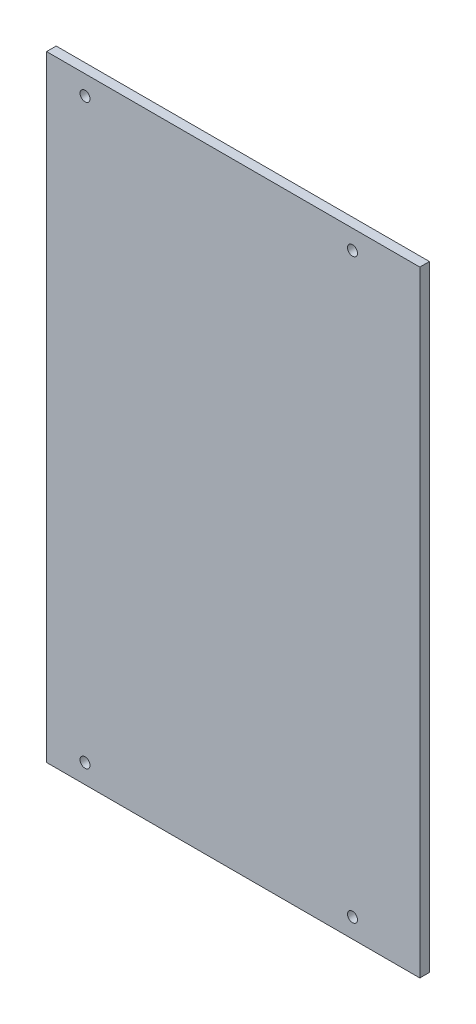
SolidWorks part; units mm, degrees
ref_plane "前视基准面" through (0, 0, 0) normal (0, 0, 1) x (1, 0, 0)
ref_plane "上视基准面" through (0, 0, 0) normal (0, 1, 0) x (1, 0, 0)
ref_plane "右视基准面" through (0, 0, 0) normal (1, 0, 0) x (0, 0, -1)
sketch "草图1" plane through (0, 0, 0) normal (0, 0, 1) x (1, 0, 0)
  line L0 (0, 0) -> (0, 320)
  line L1 (0, 320) -> (194, 320)
  line L2 (194, 320) -> (194, 0)
  line L3 (194, 0) -> (0, 0)
  circle A0 centre (20, 310) radius 2.6
  circle A1 centre (159, 310) radius 2.6
  circle A2 centre (159, 10) radius 2.6
  circle A4 centre (20, 10) radius 2.6
  point P8 (0, 0)
  point P11 (11.3359, -10.698)
  dimension "D4" = 5.2
  dimension "D6" = 2
  dimension "D7" = 2
  dimension "D1" = 320
  dimension "D2" = 194
  dimension "D3" = 20
  dimension "D5" = 10
  dimension "D8" = 35
  dimension "D9" = 35
  dimension "D10" = 10
  dimension "D11" = 10
  dimension "D12" = 10
extrude "凸台-拉伸1" add sketch "草图1" along normal blind 5
